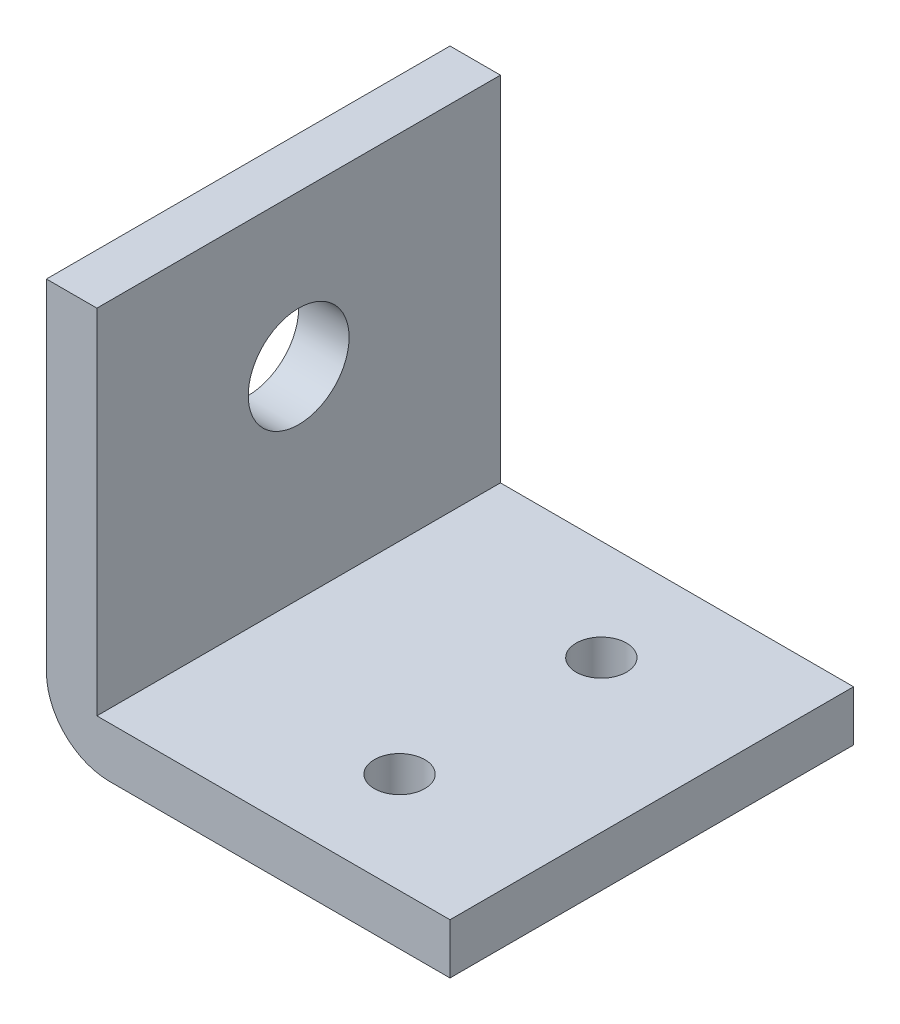
SolidWorks part; units mm, degrees
ref_plane "Front Plane" through (0, 0, 0) normal (0, 0, 1) x (1, 0, 0)
ref_plane "Top Plane" through (0, 0, 0) normal (0, 1, 0) x (1, 0, 0)
ref_plane "Right Plane" through (0, 0, 0) normal (1, 0, 0) x (0, 0, -1)
sketch "Sketch1" plane through (0, 0, 0) normal (0, 0, 1) x (1, 0, 0)
  line L0 (0, 40) -> (0, 0)
  line L1 (0, 0) -> (40, 0)
  line L2 (40, 0) -> (40, 5)
  line L3 (40, 5) -> (5, 5)
  line L4 (5, 5) -> (5, 40)
  line L5 (5, 40) -> (0, 40)
  dimension "D1" = 40
  dimension "D2" = 40
  dimension "D3" = 5
  dimension "D4" = 5
extrude "Boss-Extrude1" add sketch "Sketch1" along normal mid plane 40
fillet "Fillet1" radius 6.25 1 edges at (0, 0, 0)
hole_wizard "Ø10.0mm Dowel Hole1" positions "Sketch2" profile "Sketch3" hole size "Ø10.0" standard "ISO" end condition through all
sketch "Sketch2" plane through (5, 0, 0) normal (1, 0, 0) x (0, 0, -1)
  line L0 (-20, 40) -> (20, 40) construction
  line L1 (-20, 5) -> (-20, 40) construction
  point P0 (0, 25)
  dimension "D1" = 15
  dimension "D2" = 20
sketch "Sketch3" plane through (5, 25, 0) normal (0, 1, 0) x (0, 0, -1)
  line L0 (0, 0) -> (0, 5)
  line L1 (0, 5) -> (5, 5)
  line L2 (5, 5) -> (5, 0)
  line L5 (5, 0) -> (0, 0)
  line L11 (0, -6.35) -> (0, 107.95) construction
  dimension "Thru Hole Dia." = 10
  dimension "Thru Hole Depth" = 5
hole_wizard "Ø5.0mm Dowel Hole1" positions "Sketch4" profile "Sketch5" hole size "Ø5.0" standard "ISO" end condition through all
sketch "Sketch4" plane through (0, 5, 0) normal (0, 1, 0) x (1, 0, 0)
  line L0 (40, -20) -> (5, -20) construction
  line L1 (40, -20) -> (40, 20) construction
  point P0 (25, -10)
  point P2 (25, 10)
  dimension "D1" = 10
  dimension "D2" = 20
  dimension "D3" = 15
sketch "Sketch5" plane through (25, 5, 10) normal (1, 0, 0) x (0, 0, 1)
  line L0 (0, 0) -> (0, 5)
  line L1 (0, 5) -> (2.5, 5)
  line L2 (2.5, 5) -> (2.5, 0)
  line L5 (2.5, 0) -> (0, 0)
  line L11 (0, -6.35) -> (0, 107.95) construction
  dimension "Thru Hole Dia." = 5
  dimension "Thru Hole Depth" = 5
